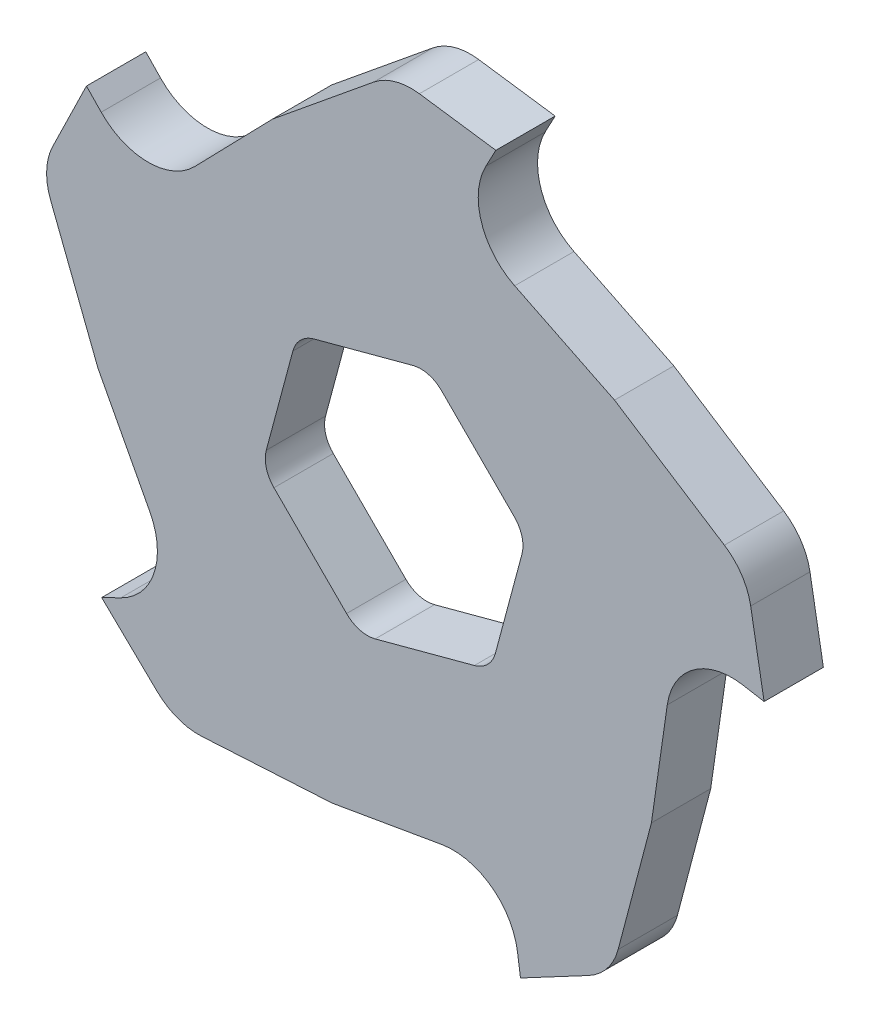
SolidWorks part; units mm, degrees
ref_plane "Front Plane" through (0, 0, 0) normal (0, 0, 1) x (1, 0, 0)
ref_plane "Top Plane" through (0, 0, 0) normal (0, 1, 0) x (1, 0, 0)
ref_plane "Right Plane" through (0, 0, 0) normal (1, 0, 0) x (0, 0, -1)
sketch "Sketch2" plane through (0, 0, 0) normal (0, 0, 1) x (1, 0, 0)
  line L0 (8.5243, 123.5742) -> (34.3126, 119.9499)
  line L1 (34.3126, 119.9499) -> (30.9469, 113.6199)
  line L2 (40.6633, 83.5495) -> (74.3339, 66.9916)
  line L3 (-6.9115, 119.2581) -> (-41.0362, 91.3835)
  line L4 (111.3894, 43.1508) -> (74.3339, 66.9916)
  line L5 (120.2642, 29.8042) -> (124.7863, 4.1581)
  line L6 (124.7863, 4.1581) -> (117.726, 5.403)
  line L7 (92.1299, -13.1301) -> (86.7872, -50.2694)
  line L8 (75.5641, -92.8785) -> (86.7872, -50.2694)
  line L9 (65.6131, -105.4432) -> (42.6197, -117.6691)
  line L10 (42.6197, -117.6691) -> (41.6219, -110.5697)
  line L11 (16.0862, -91.9534) -> (-20.8864, -98.3489)
  line L12 (-64.8781, -100.8419) -> (-20.8864, -98.3489)
  line L13 (-79.9029, -95.2608) -> (-98.6358, -77.1707)
  line L14 (-98.6358, -77.1707) -> (-92.1922, -74.0279)
  line L15 (-82.378, -43.9892) -> (-99.8856, -10.8025)
  line L16 (-115.8509, 30.2657) -> (-99.8856, -10.8025)
  line L17 (-115.1858, 46.2798) -> (-103.7698, 69.6859)
  line L18 (-103.7698, 69.6859) -> (-98.7897, 64.5289)
  line L19 (-67.1885, 64.4775) -> (-41.0362, 91.3835)
  line L20 (0, -55) -> (0, 55) construction
  line L21 (-11.9543, -44.6142) -> (32.6599, -32.6599)
  line L22 (32.6599, -32.6599) -> (44.6142, 11.9543)
  line L23 (44.6142, 11.9543) -> (11.9543, 44.6142)
  line L24 (11.9543, 44.6142) -> (-32.6599, 32.6599)
  line L25 (-32.6599, 32.6599) -> (-44.6142, -11.9543)
  line L26 (-44.6142, -11.9543) -> (-11.9543, -44.6142)
  arc A0 (111.3894, 43.1508) -> (120.2642, 29.8042) centre (100.568, 26.3313) cw
  arc A1 (30.9469, 113.6199) -> (40.6633, 83.5495) centre (50.3717, 103.2915) ccw
  arc A2 (117.726, 5.403) -> (92.1299, -13.1301) centre (113.9058, -16.2627) ccw
  arc A3 (41.6219, -110.5697) -> (16.0862, -91.9534) centre (19.836, -113.6315) ccw
  arc A4 (-92.1922, -74.0279) -> (-82.378, -43.9892) centre (-101.8363, -54.2544) ccw
  arc A5 (-98.7897, 64.5289) -> (-67.1885, 64.4775) centre (-82.9642, 79.8113) ccw
  arc A6 (8.5243, 123.5742) -> (-6.9115, 119.2581) centre (5.7408, 103.7688) ccw
  arc A7 (-115.8509, 30.2657) -> (-115.1858, 46.2798) centre (-97.2099, 37.5124) cw
  arc A8 (-64.8781, -100.8419) -> (-79.9029, -95.2608) centre (-66.0097, -80.874) cw
  arc A9 (75.5641, -92.8785) -> (65.6131, -105.4432) centre (56.2237, -87.7843) cw
  circle A10 centre (0, 0) radius 40 construction
  point P34 (-0.1374, -0.2092)
  dimension "D2" = 22
  dimension "D4" = 20
  dimension "D5" = 80
  dimension "D1" = 70
  dimension "D3" = 6.33
  dimension "D6" = 45
extrude "Boss-Extrude1" add sketch "Sketch2" along normal blind 20
fillet "Fillet1" radius 10 6 edges at (32.6599, -32.6599, 10) (44.6142, 11.9543, 10) (11.9543, 44.6142, 10) (-32.6599, 32.6599, 10) (-44.6142, -11.9543, 10) (-11.9543, -44.6142, 10)
